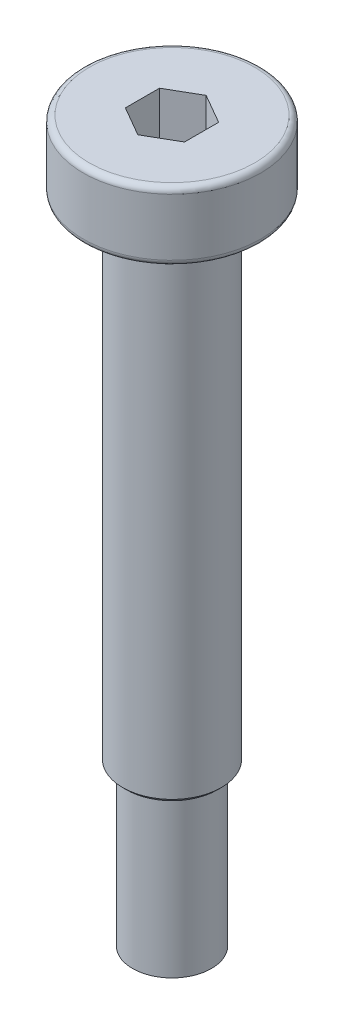
SolidWorks part; units mm, degrees
ref_plane "前视基准面" through (0, 0, 0) normal (0, 0, 1) x (1, 0, 0)
ref_plane "上视基准面" through (0, 0, 0) normal (0, 1, 0) x (1, 0, 0)
ref_plane "右视基准面" through (0, 0, 0) normal (1, 0, 0) x (0, 0, -1)
other "Configuration Table"
sketch "草图1" plane through (0, 0, 0) normal (0, 0, 1) x (1, 0, 0)
  line L0 (0, 3.5) -> (0, -12.3937) construction
  line L1 (0, 3.5) -> (-4.5, 3.5)
  line L2 (-4.5, 3.5) -> (-4.5, 0)
  line L3 (-4.5, 0) -> (-2.5, 0)
  line L4 (-2.5, 0) -> (-2.5, -25)
  line L5 (-2.5, -25) -> (-2, -25)
  line L6 (-2, -25) -> (-2, -33)
  line L7 (-2, -33) -> (0, -33)
  line L8 (0, 3.5) -> (0, -33)
  dimension "D1" = 9
  dimension "D2" = 3.5
  dimension "D3" = 25
  dimension "D4" = 5
  dimension "D5" = 4
  dimension "D6" = 8
revolve "旋转1" add sketch "草图1" angle 360 about L0
cosmetic thread "装饰螺纹线1" parameters "D2"=3.242
fillet "圆角1" radius 0.3 2 edges at (-4.5, 0, 0) (-4.5, 3.5, 0)
sketch "草图2" plane through (0, 3.5, 0) normal (0, 1, 0) x (1, 0, 0)
  line L1 (1.5, -0.866) -> (1.5, 0.866)
  line L2 (1.5, 0.866) -> (0, 1.7321)
  line L3 (0, 1.7321) -> (-1.5, 0.866)
  line L4 (-1.5, 0.866) -> (-1.5, -0.866)
  line L5 (-1.5, -0.866) -> (0, -1.7321)
  line L6 (0, -1.7321) -> (1.5, -0.866)
  circle A0 centre (0, 0) radius 1.5 construction
  dimension "D1" = 3
extrude "切除-拉伸1" cut sketch "草图2" against normal blind 2.4 contours L1 L2 L3 L4 L5 L6
chamfer "倒角1" distance 0.2 angle 45 1 edges at (-2.5, -25, 0)
